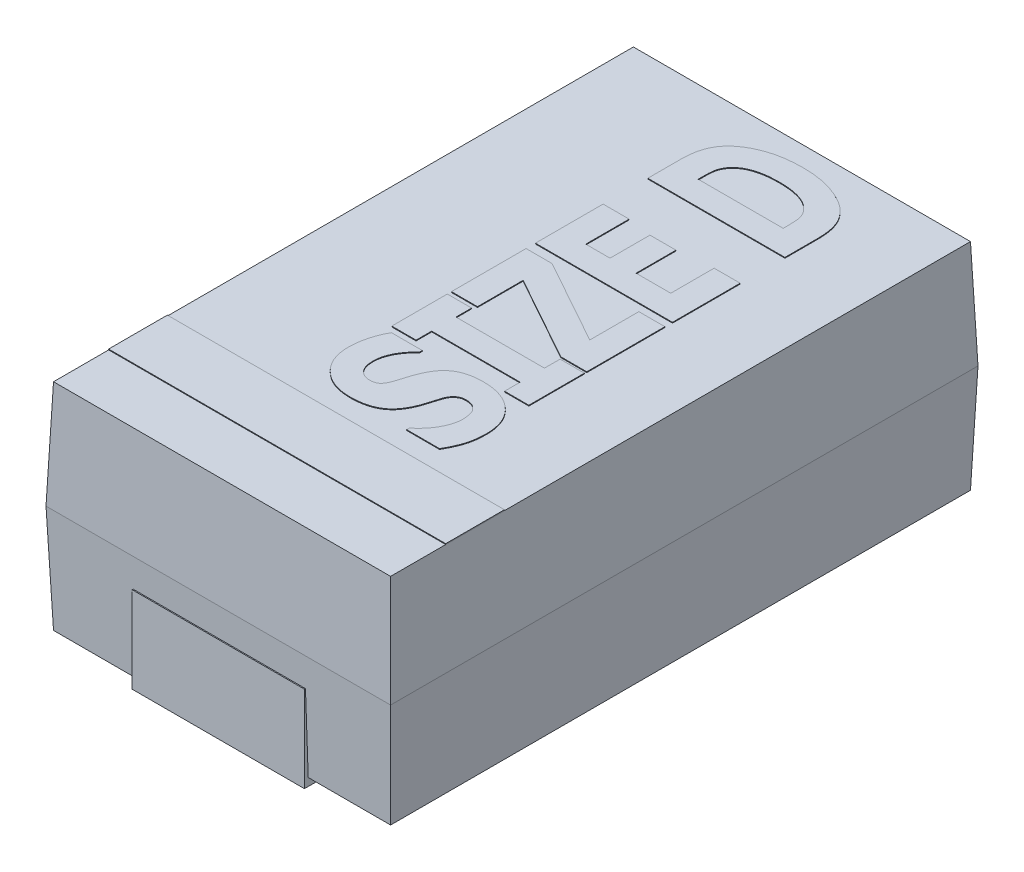
SolidWorks part; units mm, degrees
ref_plane "Front Plane" through (0, 0, 0) normal (0, 0, 1) x (1, 0, 0)
ref_plane "Top Plane" through (0, 0, 0) normal (0, 1, 0) x (1, 0, 0)
ref_plane "Right Plane" through (0, 0, 0) normal (1, 0, 0) x (0, 0, -1)
sketch "Sketch1" plane through (0, 0, 0) normal (0, 1, 0) x (1, 0, 0)
  line L1 (-2.2, 3.75) -> (2.2, 3.75)
  line L2 (-2.2, 3.75) -> (-2.2, -3.75)
  line L3 (-2.2, -3.75) -> (2.2, -3.75)
  line L4 (2.2, 3.75) -> (2.2, -3.75)
  line L5 (-2.2, 3.75) -> (2.2, -3.75) construction
  line L6 (-2.2, -3.75) -> (2.2, 3.75) construction
  point P0 (0, 0)
  dimension "D1" = 4.4
  dimension "D2" = 7.5
extrude "Boss-Extrude1" add sketch "Sketch1" along normal mid plane 2.75 draft 2
sketch "Sketch2" plane through (0, -1.375, 0) normal (0, -1, 0) x (1, 0, 0)
  line L0 (0, 0) -> (3.8147, 0) construction
  line L1 (-1.1, 3.75) -> (1.1, 3.75)
  line L2 (-1.1, 3.75) -> (-1.1, 2.4)
  line L3 (-1.1, 2.4) -> (1.1, 2.4)
  line L4 (1.1, 3.75) -> (1.1, 2.4)
  line L5 (-1.1, 3.75) -> (1.1, 2.4) construction
  line L6 (-1.1, 2.4) -> (1.1, 3.75) construction
  line L7 (-1.1, -2.4) -> (1.1, -2.4)
  line L8 (1.1, -3.75) -> (1.1, -2.4)
  line L9 (-1.1, -3.75) -> (1.1, -3.75)
  line L10 (-1.1, -3.75) -> (-1.1, -2.4)
  line L11 (0, 2.4) -> (0, -2.4) construction
  point P0 (0, 3.075)
  dimension "D1" = 2.2
  dimension "D2" = 1.35
  dimension "D3" = 7.5
extrude "Boss-Extrude2" add sketch "Sketch2" along normal blind 0.1 and the other way blind 1
sketch "Sketch3" plane through (0, 1.375, 0) normal (0, 1, 0) x (1, 0, 0)
  line L0 (-2.152, -2.6235) -> (2.152, -2.6235)
  line L1 (-2.152, 3.702) -> (-2.152, -3.702) construction
  line L2 (2.152, -3.702) -> (2.152, 3.702) construction
extrude "Extrude-Thin1" add sketch "Sketch3" along normal blind 0.01 thin thin type mid plane wall 0.75
sketch "Sketch4" plane through (0, 1.375, 0) normal (0, 1, 0) x (1, 0, 0)
  line L0 (1.152, -2.2485) -> (1.152, 3.702) construction
  line L1 (2.152, 3.702) -> (-2.152, 3.702) construction
  line L2 (2.152, -2.2485) -> (2.152, 3.702) construction
  line L3 (-2.152, -2.2485) -> (2.152, -2.2485) construction
  text T0 "SIZE D" font "Verdana" height 1.75
  dimension "D1" = 1
extrude "Boss-Extrude3" add sketch "Sketch4" along normal blind 0.01
